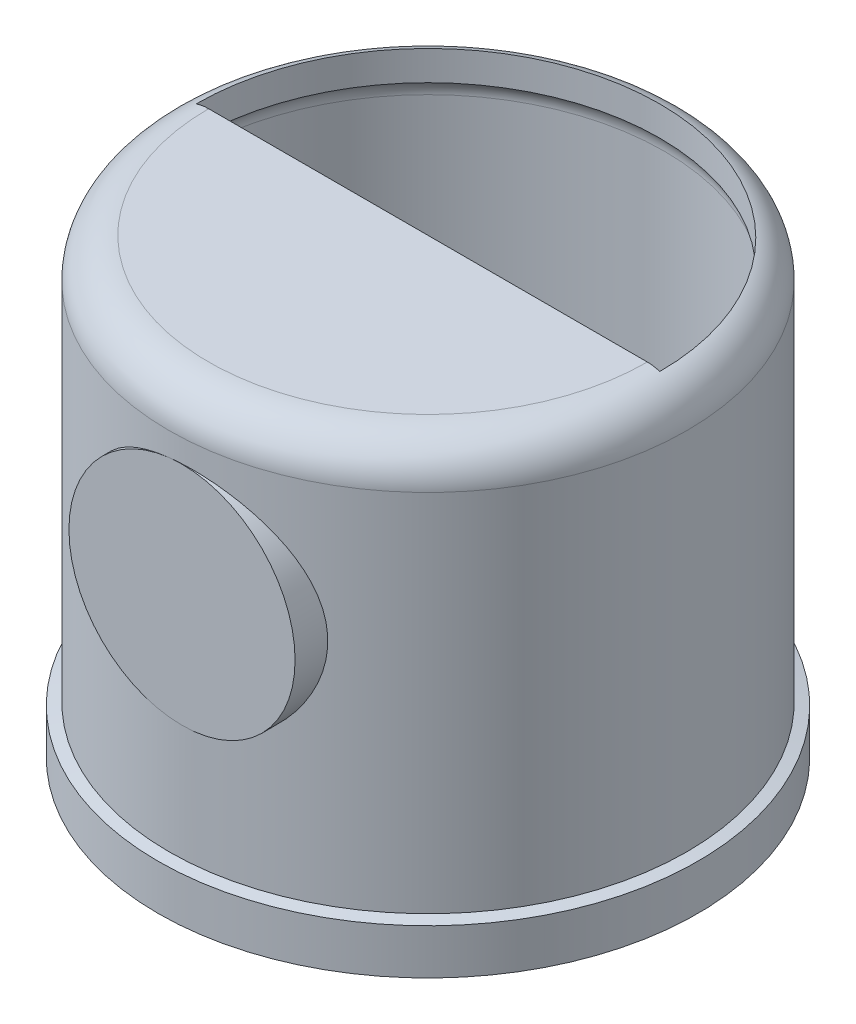
SolidWorks part; units mm, degrees
ref_plane "Front Plane" through (0, 0, 0) normal (0, 0, 1) x (1, 0, 0)
ref_plane "Top Plane" through (0, 0, 0) normal (0, 1, 0) x (1, 0, 0)
ref_plane "Right Plane" through (0, 0, 0) normal (1, 0, 0) x (0, 0, -1)
sketch "Sketch1" plane through (0, 0, 0) normal (0, 0, 1) x (1, 0, 0)
  line L0 (0, -0.7241) -> (0, 49.8133) construction
  line L1 (20.9, 0) -> (23.8716, 0)
  line L2 (23.8716, 0) -> (23.8716, 4)
  line L3 (23.8716, 4) -> (22.9, 4.2367)
  line L4 (22.9, 4.2367) -> (22.9, 36.5)
  line L5 (19.4, 40) -> (0, 40)
  line L6 (20.9, 0) -> (20.9, 11.9082)
  line L7 (18.9, 38) -> (0, 38)
  line L8 (0, 38) -> (0, 40)
  line L9 (20.9, 13.9082) -> (20.9, 36)
  line L10 (20.9, 13.9082) -> (0, 13.9082)
  line L12 (20.9, 11.9082) -> (0, 11.9082)
  line L13 (0, 13.9082) -> (0, 11.9082)
  arc A0 (22.9, 36.5) -> (19.4, 40) centre (19.4, 36.5) ccw
  arc A1 (20.9, 36) -> (18.9, 38) centre (18.9, 36) ccw
  point P11 (22.9, 40)
  dimension "D8" = 3.5
  dimension "D9" = 2
  dimension "D1" = 2
  dimension "D2" = 4
  dimension "D3" = 1
  dimension "D4" = 40
  dimension "D5" = 22.9
  dimension "D6" = 2
  dimension "D7" = 2.9716
  dimension "D10" = 2
revolve "Revolve1" add sketch "Sketch1" angle 360 about L0
ref_plane "Plane1" through (0, 4, 0) normal (0, 1, 0) x (1, 0, 0)
sketch "Sketch3" plane through (0, 0, 0) normal (0, 0, 1) x (1, 0, 0)
  point P0 (1.2404, 19.1989)
ref_point "Point1"
ref_plane "Plane2" through (0, 0, 22.9) normal (0, 0, 1) x (1, 0, 0)
sketch "Sketch4" plane through (0, 0, 22.9) normal (0, 0, 1) x (1, 0, 0)
  line L0 (22.9, 36.5) -> (-22.9, 36.5) construction
  circle A1 centre (1.1446, 24.5) radius 10
  dimension "D1" = 20
  dimension "D2" = 12
extrude "Boss-Extrude2" add sketch "Sketch4" against normal blind 6
ref_plane "Plane3" through (0, 0, 16.9) normal (0, 0, -1) x (-1, 0, 0)
ref_plane "Plane4" through (0, 40, 0) normal (0, 1, 0) x (1, 0, 0)
sketch "Sketch9" plane through (0, 40, 0) normal (0, 1, 0) x (1, 0, 0)
  line L0 (-20.5, 0) -> (20.5, 0)
  arc A0 (20.5, 0) -> (-20.5, 0) centre (0, 0) ccw
  dimension "D1" = 41
extrude "Cut-Extrude2" cut sketch "Sketch9" against normal blind 30
